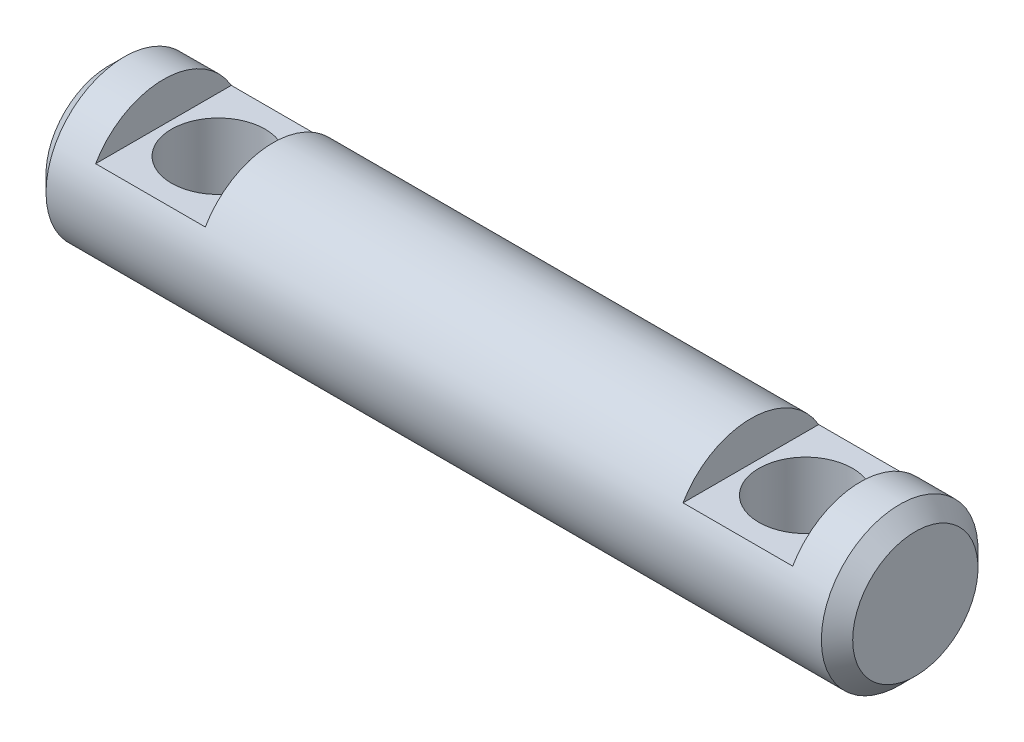
SolidWorks part; units mm, degrees
ref_plane "Front Plane" through (0, 0, 0) normal (0, 0, 1) x (1, 0, 0)
ref_plane "Top Plane" through (0, 0, 0) normal (0, 1, 0) x (1, 0, 0)
ref_plane "Right Plane" through (0, 0, 0) normal (1, 0, 0) x (0, 0, -1)
sketch "Sketch1" plane through (0, 0, 0) normal (0, 0, 1) x (1, 0, 0)
  line L5 (-103, 0) -> (0, 0)
  line L6 (-103, 0) -> (-103, 10)
  line L7 (-103, 10) -> (0, 10)
  line L8 (0, 0) -> (0, 10)
  line L9 (-103, 0) -> (0, 10) construction
  line L10 (-103, 10) -> (0, 0) construction
  point P0 (-51.5, 5)
  dimension "D1" = 103
  dimension "D2" = 10
revolve "Revolve1" add sketch "Sketch1" angle 360 about L5
sketch "Sketch2" plane through (0, 0, 0) normal (1, 0, 0) x (0, 0, -1)
  line L0 (-10.8723, 5) -> (10.8723, 5)
  arc A3 (10.8723, 5) -> (-10.8723, 5) centre (0, 0) ccw
  dimension "D1" = 5
extrude "Cut-Extrude1" cut sketch "Sketch2" against normal blind 14 from offset 7 contours A3 L0 offset against normal yes
sketch "Sketch3" plane through (-103, 0, 0) normal (-1, 0, 0) x (0, 0, 1)
  line L1 (-15, 5) -> (15, 5)
  arc A0 (15, 5) -> (-15, 5) centre (0, 0) ccw
  dimension "D2" = 30
  dimension "D1" = 5
extrude "Cut-Extrude2" cut sketch "Sketch3" against normal blind 14 from offset 7 offset against normal yes
sketch "Sketch4" plane through (0, 0, 0) normal (0, 1, 0) x (1, 0, 0)
  circle A0 centre (-89, 0) radius 5.983
  circle A1 centre (-14, 0) radius 5.983
  dimension "D1" = 11.966
  dimension "D2" = 11.966
  dimension "D3" = 75
extrude "Cut-Extrude3" cut sketch "Sketch4" against normal through all both and the other way through all
chamfer "Chamfer1" distance 2 angle 45 2 edges at (0, 0, 10) (-103, 0, 10)
